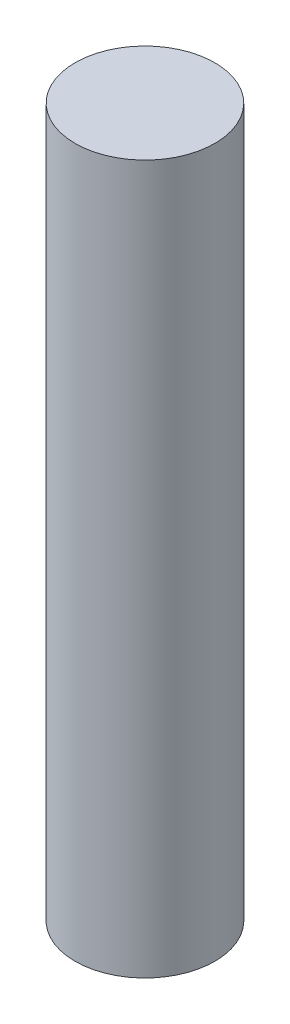
SolidWorks part; units mm, degrees
ref_plane "Front Plane" through (0, 0, 0) normal (0, 0, 1) x (1, 0, 0)
ref_plane "Top Plane" through (0, 0, 0) normal (0, 1, 0) x (1, 0, 0)
ref_plane "Right Plane" through (0, 0, 0) normal (1, 0, 0) x (0, 0, -1)
sketch "Sketch1" plane through (0, 0, 0) normal (0, 1, 0) x (1, 0, 0)
  circle A0 centre (0, 0) radius 14.8
  dimension "D1" = 29.6
extrude "Boss-Extrude1" add sketch "Sketch1" along normal blind 150
